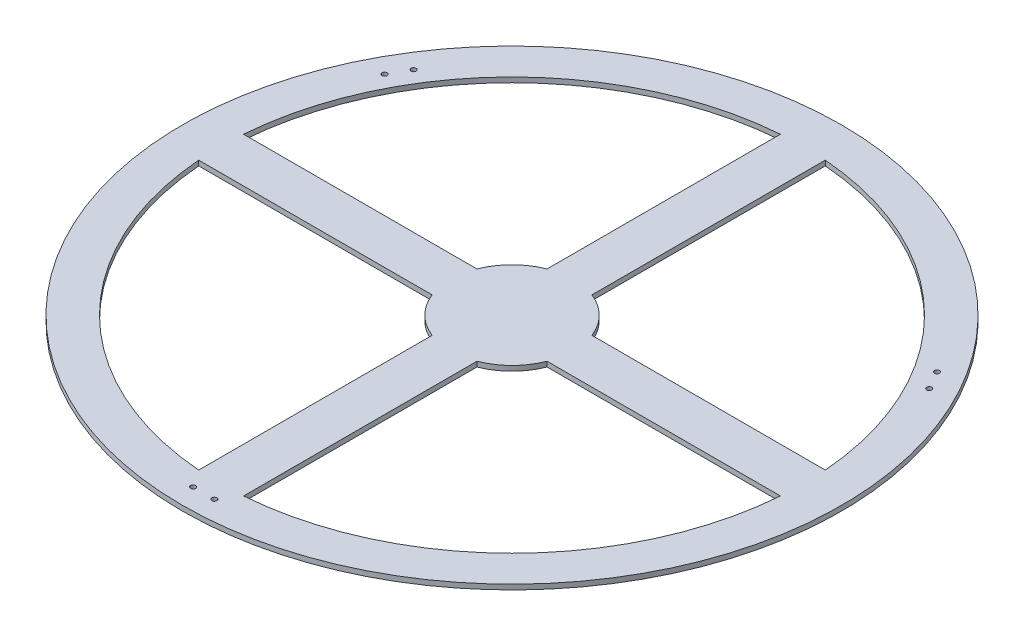
SolidWorks part; units mm, degrees
material "Maple"
ref_plane "Front Plane" through (0, 0, 0) normal (0, 0, 1) x (1, 0, 0)
ref_plane "Top Plane" through (0, 0, 0) normal (0, 1, 0) x (1, 0, 0)
ref_plane "Right Plane" through (0, 0, 0) normal (1, 0, 0) x (0, 0, -1)
sketch "Sketch1" plane through (0, 0, 0) normal (0, 1, 0) x (1, 0, 0)
  line L0 (479.7212, 531.9437) -> (479.7212, 347.7937) construction
  line L1 (653.4424, 518.5408) -> (514.0558, 518.5408)
  line L2 (306, 518.5408) -> (445.3865, 518.5408)
  line L3 (486.0712, 347.7937) -> (473.3712, 347.7937) construction
  line L4 (317.0676, 618.5194) -> (323.4176, 629.5179) construction
  line L5 (653.4424, 545.3465) -> (514.0558, 545.3465)
  line L6 (445.3865, 545.3465) -> (306, 545.3465)
  line L7 (479.7212, 531.9437) -> (320.2426, 624.0187) construction
  line L8 (636.0247, 629.5179) -> (642.3747, 618.5194) construction
  line L9 (466.3183, 358.2224) -> (466.3183, 497.609)
  line L10 (466.3183, 566.2783) -> (466.3183, 705.6649)
  line L11 (479.7212, 531.9437) -> (639.1997, 624.0187) construction
  line L13 (493.124, 358.2224) -> (493.124, 497.609)
  line L14 (493.124, 566.2783) -> (493.124, 705.6649)
  arc A0 (445.3865, 518.5408) -> (466.3183, 497.609) centre (479.7212, 531.9437) ccw
  arc A1 (493.124, 497.609) -> (514.0558, 518.5408) centre (479.7212, 531.9437) ccw
  arc A2 (514.0558, 545.3465) -> (493.124, 566.2783) centre (479.7212, 531.9437) ccw
  arc A3 (466.3183, 566.2783) -> (445.3865, 545.3465) centre (479.7212, 531.9437) ccw
  circle A4 centre (479.7212, 531.9437) radius 196.85
  arc A5 (306, 518.5408) -> (466.3183, 358.2224) centre (479.7212, 531.9437) ccw
  arc A6 (493.124, 358.2224) -> (653.4424, 518.5408) centre (479.7212, 531.9437) ccw
  arc A7 (653.4424, 545.3465) -> (493.124, 705.6649) centre (479.7212, 531.9437) ccw
  arc A8 (466.3183, 705.6649) -> (306, 545.3465) centre (479.7212, 531.9437) ccw
  circle A9 centre (473.3712, 347.7937) radius 1.5
  circle A10 centre (486.0712, 347.7937) radius 1.5
  circle A11 centre (323.4176, 629.5179) radius 1.5
  circle A12 centre (317.0676, 618.5194) radius 1.5
  circle A13 centre (642.3747, 618.5194) radius 1.5
  circle A14 centre (636.0247, 629.5179) radius 1.5
  point P4 (479.7212, 347.7937)
  dimension "D1" = 184.15
  dimension "D2" = 393.7
  dimension "D4" = 3
  dimension "D5" = 3
  dimension "D3" = 12.7
  dimension "D6" = 3
extrude "Boss-Extrude1" add sketch "Sketch1" along normal blind 3
